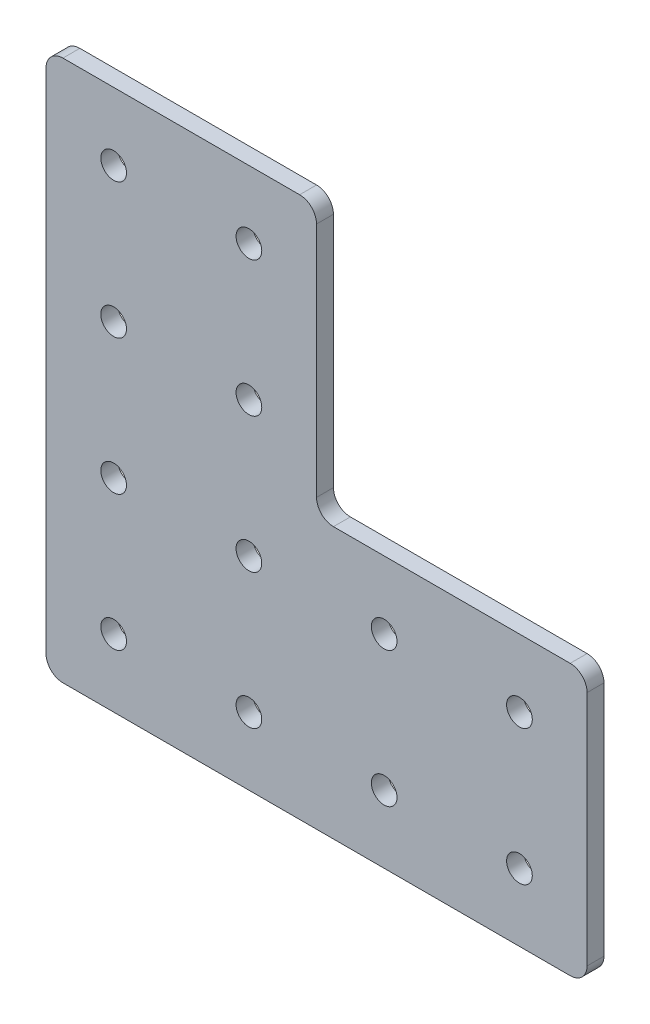
SolidWorks part; units mm, degrees
material "6061-T6 (SS)"
ref_plane "Front Plane" through (0, 0, 0) normal (0, 0, 1) x (1, 0, 0)
ref_plane "Top Plane" through (0, 0, 0) normal (0, 1, 0) x (1, 0, 0)
ref_plane "Right Plane" through (0, 0, 0) normal (1, 0, 0) x (0, 0, -1)
sketch "Sketch1" plane through (0, 0, 0) normal (0, 0, 1) x (1, 0, 0)
  line L0 (0, 0) -> (101.6, 0)
  line L1 (101.6, 0) -> (101.6, 50.8)
  line L2 (101.6, 50.8) -> (50.8, 50.8)
  line L3 (50.8, 50.8) -> (50.8, 101.6)
  line L4 (50.8, 101.6) -> (0, 101.6)
  line L5 (0, 101.6) -> (0, 0)
  line L6 (50.8, 50.8) -> (50.8, 0) construction
  line L7 (50.8, 50.8) -> (0, 50.8) construction
  line L9 (12.7, 88.9) -> (38.1, 88.9) construction
  line L10 (12.7, 88.9) -> (12.7, 63.5) construction
  line L11 (12.7, 63.5) -> (38.1, 63.5) construction
  line L12 (38.1, 88.9) -> (38.1, 63.5) construction
  circle A0 centre (12.7, 88.9) radius 2.413
  circle A1 centre (38.1, 88.9) radius 2.413
  circle A2 centre (38.1, 63.5) radius 2.413
  circle A3 centre (12.7, 63.5) radius 2.413
  circle A4 centre (38.1, 12.7) radius 2.413
  circle A5 centre (38.1, 38.1) radius 2.413
  circle A6 centre (12.7, 38.1) radius 2.413
  circle A7 centre (12.7, 12.7) radius 2.413
  circle A8 centre (88.9, 12.7) radius 2.413
  circle A9 centre (63.5, 12.7) radius 2.413
  circle A10 centre (63.5, 38.1) radius 2.413
  circle A11 centre (88.9, 38.1) radius 2.413
  dimension "D5" = 4.826
  dimension "D7" = 12.7
  dimension "D1" = 50.8
  dimension "D2" = 50.8
  dimension "D3" = 101.6
  dimension "D4" = 50.8
  dimension "D6" = 25.4
  dimension "D8" = 12.7
extrude "Boss-Extrude1" add sketch "Sketch1" along normal blind 3.175
fillet "Fillet1" radius 3.175 6 edges at (50.8, 101.6, 1.5875) (50.8, 50.8, 1.5875) (101.6, 50.8, 1.5875) (101.6, 0, 1.5875) (0, 0, 1.5875) (0, 101.6, 1.5875)
